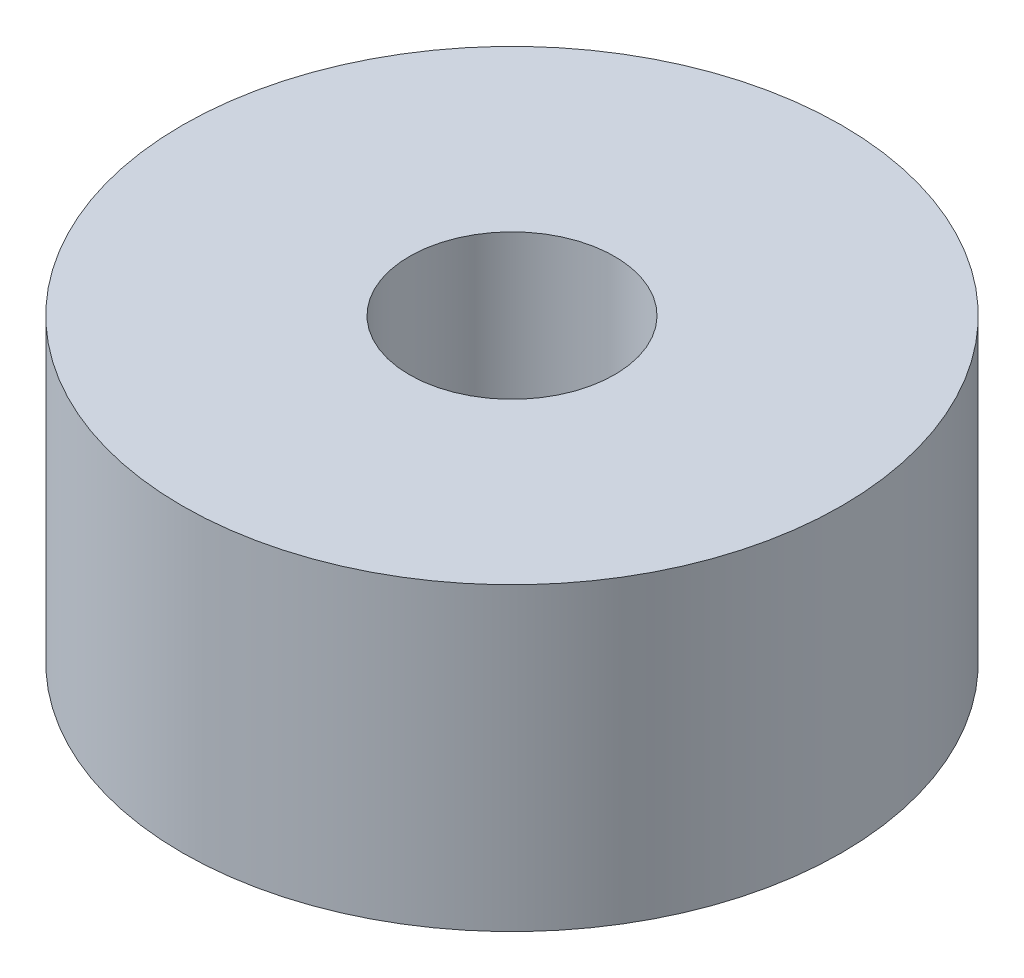
SolidWorks part; units mm, degrees
ref_plane "前基準面" through (0, 0, 0) normal (0, 0, 1) x (1, 0, 0)
ref_plane "上基準面" through (0, 0, 0) normal (0, 1, 0) x (1, 0, 0)
ref_plane "右基準面" through (0, 0, 0) normal (1, 0, 0) x (0, 0, -1)
sketch "草圖1" plane through (0, 0, 0) normal (0, 1, 0) x (1, 0, 0)
  circle A0 centre (0, 0) radius 9
  circle A1 centre (0, 0) radius 2.8
  dimension "D1" = 18
  dimension "D2" = 5.6
extrude "填料-伸長1" add sketch "草圖1" along normal mid plane 8.2
